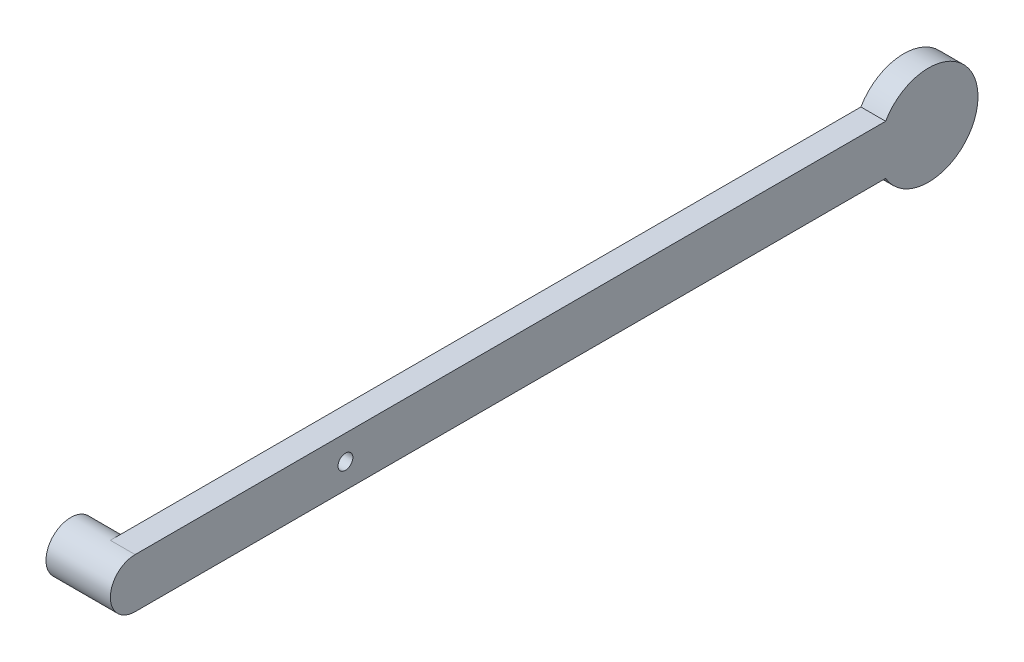
SolidWorks part; units mm, degrees
ref_plane "Plano frontal" through (0, 0, 0) normal (1, 0, 0) x (0, 1, 0)
ref_plane "Plano superior" through (0, 0, 0) normal (0, 0, 1) x (0, 1, 0)
ref_plane "Plano direito" through (0, 0, 0) normal (0, 1, 0) x (-1, 0, 0)
sketch "Esboço1" plane through (0, 0, 0) normal (1, 0, 0) x (0, 1, 0)
  line L0 (0, 42.5) -> (0, -117.8) construction
  line L1 (5, 42.5) -> (5, -117.8)
  line L2 (-5, 42.5) -> (-5, -117.8)
  arc A0 (5, 42.5) -> (-5, 42.5) centre (0, 42.5) ccw
  arc A1 (-5, -117.8) -> (5, -117.8) centre (0, -117.8) ccw
  circle A2 centre (0, 0) radius 1.5
  point P2 (0, -37.65)
  dimension "D3" = 5
  dimension "D4" = 3
  dimension "D1" = 160.3
  dimension "D2" = 42.5
extrude "Ressalto-extrusão1" add sketch "Esboço1" along normal blind 5
sketch "Esboço2" plane through (0, 0, 0) normal (-1, 0, 0) x (0, -1, 0)
  circle A0 centre (0, 42.5) radius 5
extrude "Ressalto-extrusão2" add sketch "Esboço2" along normal blind 8
sketch "Esboço3" plane through (0, 0, 0) normal (-1, 0, 0) x (0, -1, 0)
  circle A0 centre (0, -117.8) radius 10
  dimension "D1" = 20
extrude "Ressalto-extrusão3" add sketch "Esboço3" against normal up to surface (5 mm away) up to face at (5, 0, -37.65)
